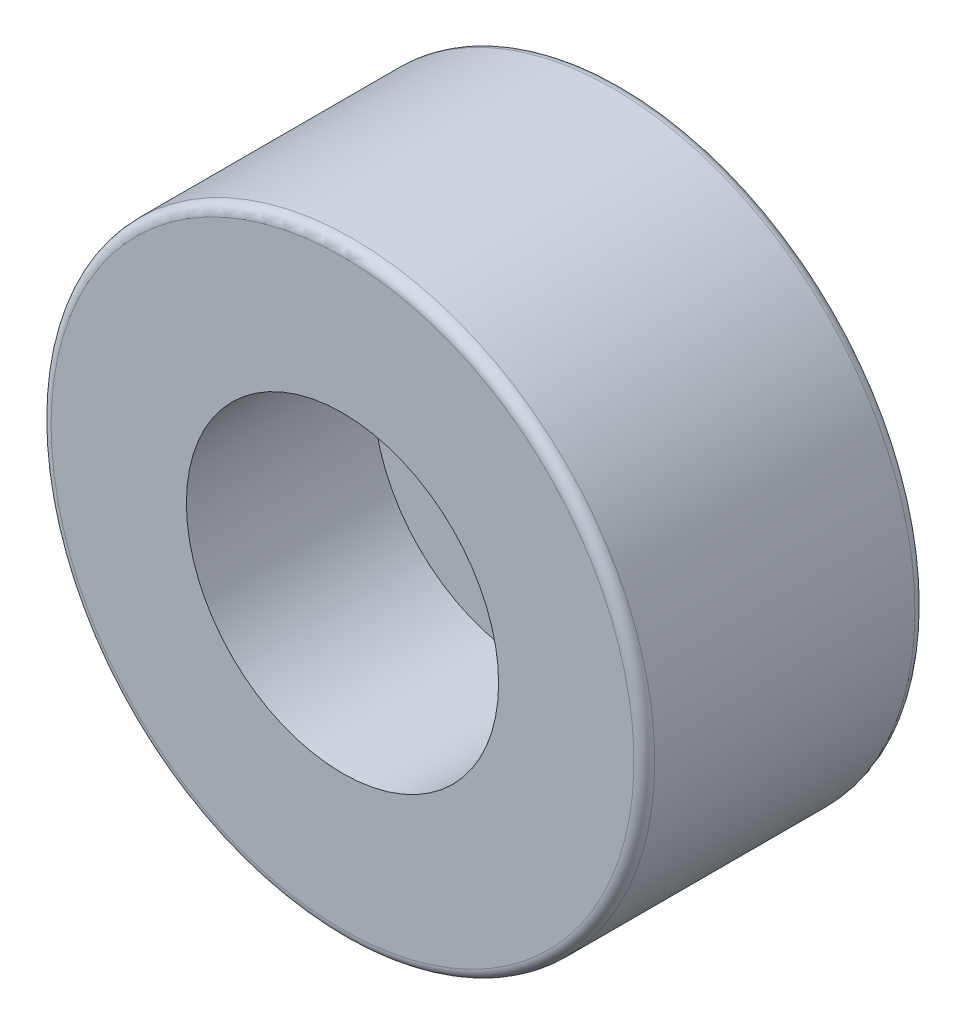
SolidWorks part; units mm, degrees
ref_plane "Спереди" through (0, 0, 0) normal (0, 0, 1) x (1, 0, 0)
ref_plane "Сверху" through (0, 0, 0) normal (0, 1, 0) x (1, 0, 0)
ref_plane "Справа" through (0, 0, 0) normal (1, 0, 0) x (0, 0, -1)
sketch "Эскиз1" plane through (0, 0, 0) normal (1, 0, 0) x (0, 0, -1)
  line L0 (0, 0) -> (4841.9406, 0) construction
  line L1 (0, 0) -> (0, 4841.9406) construction
  line L2 (0, 1.5) -> (0, 14.5)
  line L3 (0, 14.5) -> (-13.5, 14.5)
  line L4 (-13.5, 14.5) -> (-13.5, 7.5)
  line L5 (-13.5, 7.5) -> (-4.5, 7.5)
  line L6 (-4.5, 7.5) -> (-4.5, 1.5)
  line L7 (-4.5, 1.5) -> (0, 1.5)
  dimension "D1" = 3
  dimension "D2" = 29
  dimension "D3" = 13.5
  dimension "D4" = 15
  dimension "D5" = 9
revolve "Повернуть1" add sketch "Эскиз1" angle 360 about L0
fillet "Скругление1" radius 0.5 2 edges at (14.5, 0, 0) (14.5, 0, 13.5)
